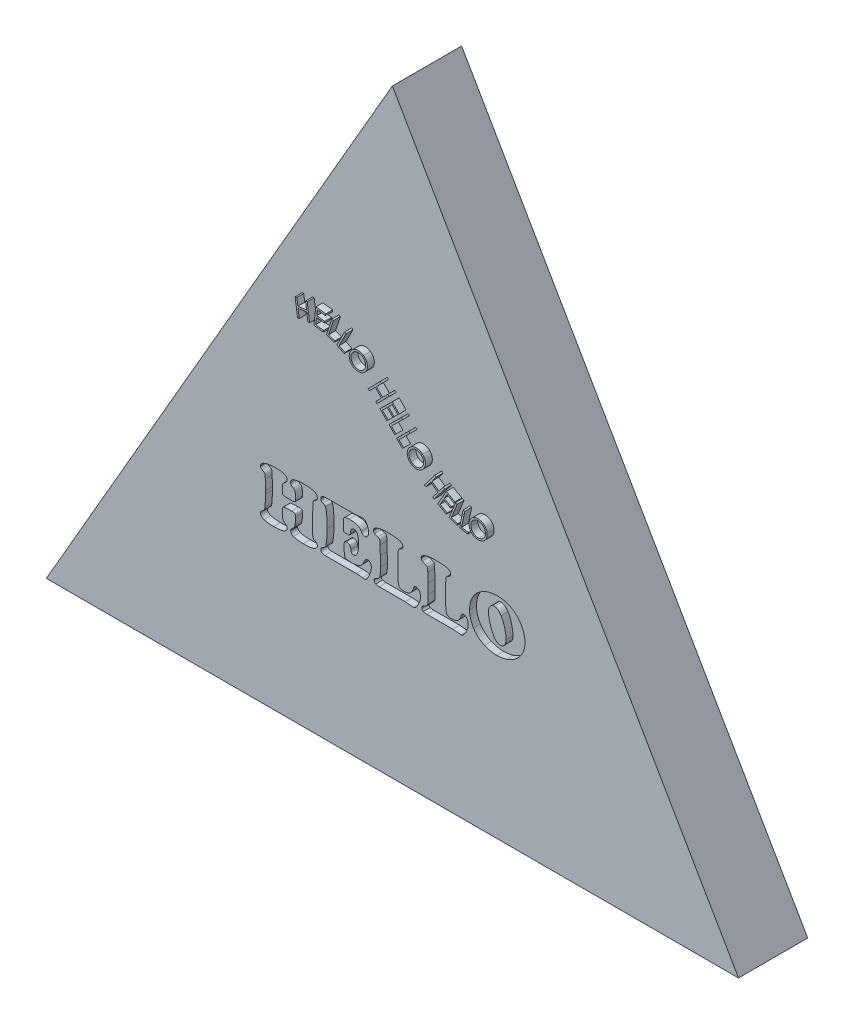
SolidWorks part; units mm, degrees
ref_plane "Front Plane" through (0, 0, 0) normal (0, 0, 1) x (1, 0, 0)
ref_plane "Top Plane" through (0, 0, 0) normal (0, 1, 0) x (1, 0, 0)
ref_plane "Right Plane" through (0, 0, 0) normal (1, 0, 0) x (0, 0, -1)
sketch "Sketch1" plane through (0, 0, 0) normal (0, 0, 1) x (1, 0, 0)
  line L0 (0, 0) -> (0, 73.3235) construction
  line L1 (0, 73.3235) -> (-63.5, -36.6617)
  line L2 (-63.5, -36.6617) -> (63.5, -36.6617)
  line L3 (63.5, -36.6617) -> (0, 73.3235)
  circle A0 centre (0, 0) radius 73.3235 construction
  dimension "D1" = 127
extrude "Boss-Extrude1" add sketch "Sketch1" along normal blind 12.7
sketch "Sketch2" plane through (0, 0, 12.7) normal (0, 0, 1) x (1, 0, 0)
  line L0 (-46.6356, -7.4517) -> (46.6356, -7.4517) construction
  line L1 (63.5, -36.6617) -> (0, 73.3235) construction
  line L2 (0, 73.3235) -> (-63.5, -36.6617) construction
  line L3 (-63.5, -36.6617) -> (63.5, -36.6617) construction
  text T0 "HELLO" font "Cooper Black" height 9.525
  point P2 (45.9318, -6.2327)
  point P5 (-46.9046, -7.9176)
  dimension "D1" = 29.21
extrude "Cut-Extrude1" cut sketch "Sketch2" against normal blind 1.27
sketch "Sketch3" plane through (0, 0, 12.7) normal (0, 0, 1) x (1, 0, 0)
  spline S0 degree 3 poles (-23.7445, 24.7729) (-1.5928, 43.9823) (3.7314, -3.8093) (26.412, 14.4612) knots 0 0 0 0 1 1 1 1 construction
  text T0 "HELLO HELLO HELLO"
  point P4 (26.412, 14.4612)
  point P6 (-23.7445, 24.7729)
extrude "Boss-Extrude2" add sketch "Sketch3" along normal blind 1.27
